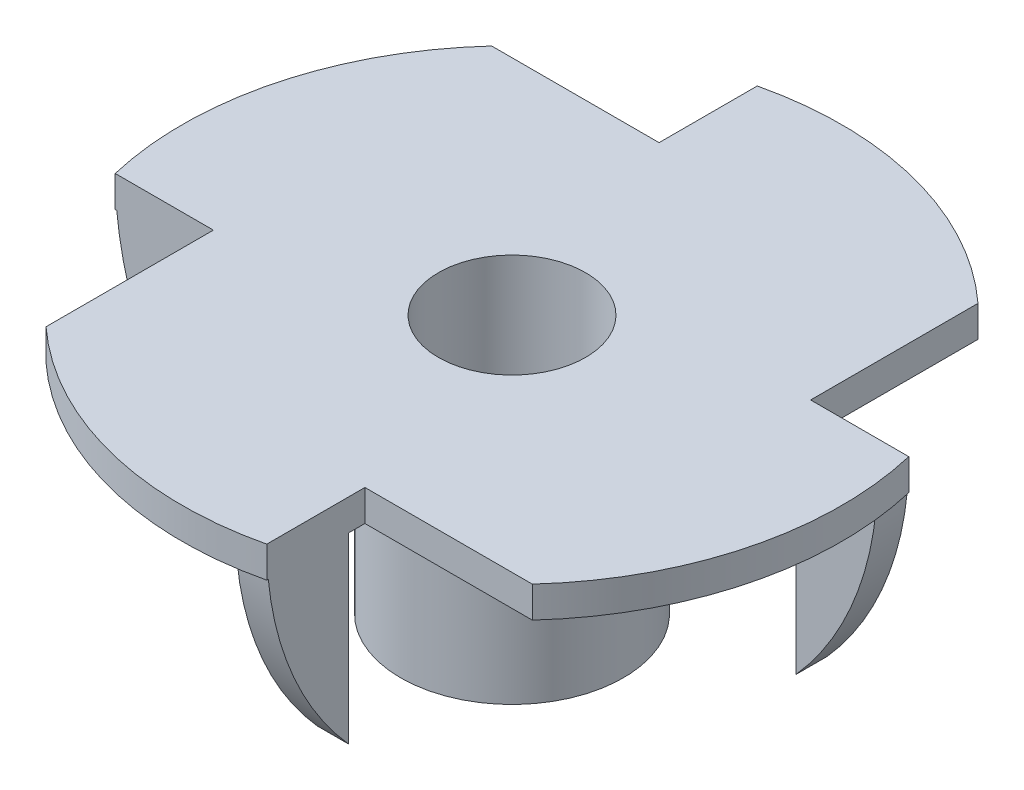
SolidWorks part; units mm, degrees
ref_plane "Plan de face" through (0, 0, 0) normal (0, 0, 1) x (1, 0, 0)
ref_plane "Plan de dessus" through (0, 0, 0) normal (0, 1, 0) x (1, 0, 0)
ref_plane "Plan de droite" through (0, 0, 0) normal (1, 0, 0) x (0, 0, -1)
sketch "Esquisse1" plane through (0, 0, 0) normal (0, 0, 1) x (1, 0, 0)
  line L0 (0, 0) -> (2.5, 0)
  line L1 (2.5, 0) -> (2.5, 5.1)
  line L2 (2.5, 5.1) -> (7.4, 5.1)
  line L3 (7.4, 5.1) -> (7.4, 5.8)
  line L4 (7.4, 5.8) -> (0, 5.8)
  line L5 (0, 0) -> (0, 5.8) construction
  line L6 (0, 0) -> (0, 5.8)
  dimension "D1" = 7.4
  dimension "D2" = 2.5
  dimension "D3" = 5.8
  dimension "D4" = 0.7
revolve "Révolution1" add sketch "Esquisse1" angle 360 about L5
hole_wizard "Trou taraudé M41" positions "Esquisse3" profile "Esquisse2" tap size "M4" standard "ISO"
sketch "Esquisse3" plane through (0, 5.8, 0) normal (0, 1, 0) x (1, 0, 0)
  point P2 (0, 0)
sketch "Esquisse2" plane through (0, 5.8, 0) normal (1, 0, 0) x (0, 0, 1)
  line L0 (0, 0) -> (0, 12.4914)
  line L1 (0, 12.4914) -> (1.65, 11.5)
  line L2 (1.65, 11.5) -> (1.65, 0)
  line L5 (1.65, 0) -> (0, 0)
  line L10 (0, 12.4914) -> (-1.65, 11.5) construction
  line L11 (0, -6.35) -> (0, 107.95) construction
  dimension "Diamètre du trou pour taraudage" = 3.3
  dimension "Profondeur du trou pour taraudage" = 11.5
  dimension "Angle de pointe" = 118
cosmetic thread "Filetage de perçage1" parameters "D1"=5.8, "D2"=4
sketch "Esquisse4" plane through (0, 5.8, 0) normal (0, 1, 0) x (1, 0, 0)
  line L0 (1.7, -5) -> (6.71, -5)
  line L1 (5, 1.7) -> (8.3954, 1.7)
  line L2 (5, 1.7) -> (5, 6.71)
  line L3 (5, 6.71) -> (8.3954, 6.71)
  line L4 (8.3954, 1.7) -> (8.3954, 6.71)
  line L5 (1.7, -5) -> (1.7, -8.3954)
  line L6 (1.7, -8.3954) -> (6.71, -8.3954)
  line L7 (6.71, -5) -> (6.71, -8.3954)
  line L8 (-5, -1.7) -> (-5, -6.71)
  line L9 (-5, -1.7) -> (-8.3954, -1.7)
  line L10 (-8.3954, -1.7) -> (-8.3954, -6.71)
  line L11 (-5, -6.71) -> (-8.3954, -6.71)
  line L12 (-1.7, 5) -> (-6.71, 5)
  line L13 (-1.7, 5) -> (-1.7, 8.3954)
  line L14 (-1.7, 8.3954) -> (-6.71, 8.3954)
  line L15 (-6.71, 5) -> (-6.71, 8.3954)
  point P19 (0, 0)
  dimension "D2" = 5
  dimension "D3" = 6.7
  dimension "D1" = 4
extrude "Enlèv. mat.-Extru.1" cut sketch "Esquisse4" against normal blind 10
sketch "Esquisse5" plane through (0, 0, -1.7) normal (0, 0, -1) x (-1, 0, 0)
  line L1 (-5.3694, 1) -> (-5.3694, 5.8)
  line L2 (-5, 5.8) -> (-7.2021, 5.8) construction
  line L3 (-5.3694, 5.8) -> (-7.2021, 5.8)
  line L4 (0, 0) -> (0, 9.7749) construction
  arc A0 (-7.2021, 5.8) -> (-5.3694, 1) centre (0, 5.8) ccw
  dimension "D1" = 4.8
extrude "Boss.-Extru.1" add sketch "Esquisse5" against normal blind 0.7
pattern_circular "Répétition circulaire1" count 4 every 90 about axis through (0, 0, 0) along (0, 1, 0) of "Boss.-Extru.1"
